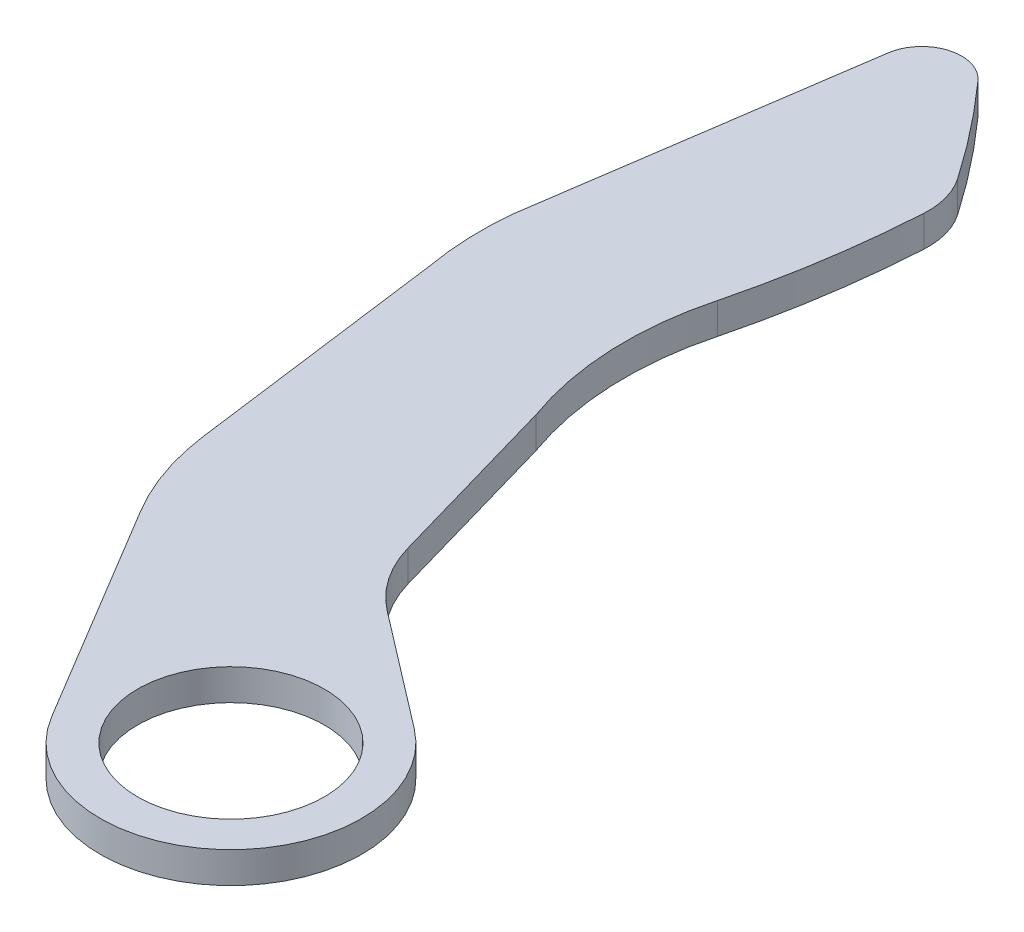
SolidWorks part; units mm, degrees
ref_plane "Front Plane" through (0, 0, 0) normal (0, 0, 1) x (1, 0, 0)
ref_plane "Top Plane" through (0, 0, 0) normal (0, 1, 0) x (1, 0, 0)
ref_plane "Right Plane" through (0, 0, 0) normal (1, 0, 0) x (0, 0, -1)
sketch "Sketch1" plane through (0, 0, 0) normal (0, 1, 0) x (1, 0, 0)
  line L42 (12.7669, 16.6735) -> (-5.8063, 30.895)
  line L43 (-12.8731, 41.2636) -> (-21.1395, 70.1022)
  line L44 (-43.1946, 148.7152) -> (-50.9327, 96.0562)
  line L45 (-50.3835, 82.3644) -> (-44.8249, 40.292)
  line L46 (-39.4657, 24.9456) -> (-18.0055, -10.8075)
  arc A148 (-22.4566, 100.5997) -> (-21.1395, 70.1022) centre (26.9938, 87.458) ccw
  arc A149 (-22.4566, 100.5997) -> (-18.0206, 129.2968) centre (-171.2572, 138.2924) ccw
  arc A150 (-18.0206, 129.2968) -> (-20.1164, 136.8055) centre (-30, 130) ccw
  arc A151 (-20.1164, 136.8055) -> (-32.0981, 152.0476) centre (-146.5445, 49.7519) ccw
  arc A152 (-32.0981, 152.0476) -> (-43.1946, 148.7152) centre (-36.8667, 147.7853) ccw
  arc A153 (-50.9327, 96.0562) -> (-50.3835, 82.3644) centre (0.0072, 91.2427) ccw
  circle A154 centre (0, 0) radius 15
  arc A155 (12.7669, 16.6735) -> (-18.0055, -10.8075) centre (0, 0) cw
  arc A156 (-5.8063, 30.895) -> (-12.8731, 41.2636) centre (6.3527, 46.7745) cw
  arc A157 (-44.8249, 40.292) -> (-39.4657, 24.9456) centre (-5.1695, 45.5313) ccw
  point P7 (-11.0524, 34.9119)
  point P11 (-43.7376, 32.0627)
  dimension "D3" = 12
  dimension "D4" = 30
  dimension "D5" = 6
  dimension "D8" = 20
  dimension "D10" = 40
  dimension "D1" = 130
  dimension "D2" = 30
  dimension "D6" = 50
  dimension "D7" = 30
  dimension "D9" = 30
extrude "Boss-Extrude2" add sketch "Sketch1" along normal blind 5
sketch "Sketch2" plane through (0, 5, 0) normal (0, 1, 0) x (1, 0, 0)
  line L0 (12.7669, 16.6735) -> (-5.8063, 30.895) construction
  point P0 (11.1334, 17.9243)
  point P1 (0, 0)
